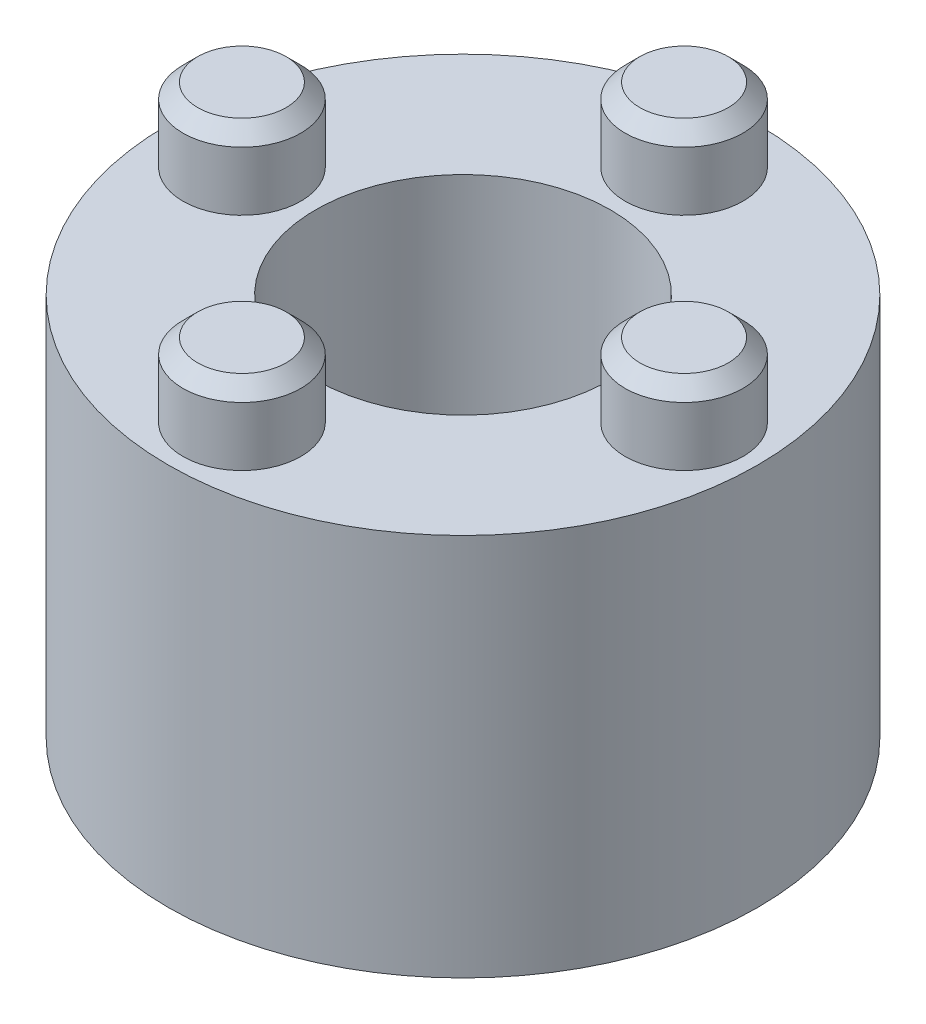
SolidWorks part; units mm, degrees
material "不锈钢 (铁素体)"
ref_plane "前视基准面" through (0, 0, 0) normal (0, 0, 1) x (1, 0, 0)
ref_plane "上视基准面" through (0, 0, 0) normal (0, 1, 0) x (1, 0, 0)
ref_plane "右视基准面" through (0, 0, 0) normal (1, 0, 0) x (0, 0, -1)
sketch "草图1" plane through (0, 0, 0) normal (0, 1, 0) x (1, 0, 0)
  circle A0 centre (0, 0) radius 10
  circle A1 centre (0, 0) radius 5
  dimension "D1" = 10
  dimension "D2" = 20
extrude "凸台-拉伸1" add sketch "草图1" along normal blind 13
sketch "草图2" plane through (0, 13, 0) normal (0, 1, 0) x (1, 0, 0)
  circle A0 centre (0, 0) radius 7.5 construction
  circle A1 centre (0, 7.5) radius 2
  circle A2 centre (7.5, 0) radius 2
  circle A3 centre (0, -7.5) radius 2
  circle A4 centre (-7.5, 0) radius 2
  point P14 (0, 0)
  dimension "D1" = 15
  dimension "D2" = 4
extrude "凸台-拉伸2" add sketch "草图2" along normal blind 2.5
chamfer "倒角1" distance 0.5 angle 45 4 edges at (7.5, 15.5, 2) (0, 15.5, 9.5) (-7.5, 15.5, 2) (0, 15.5, -5.5)
